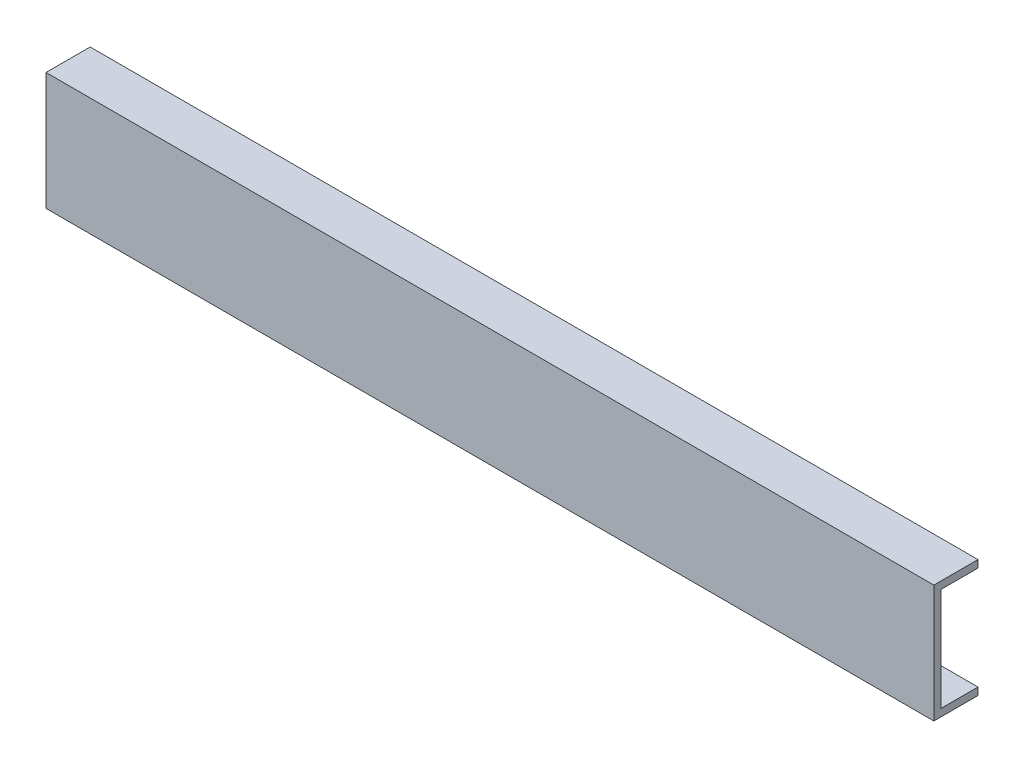
SolidWorks part; units mm, degrees
ref_plane "Front Plane" through (0, 0, 0) normal (0, 0, 1) x (1, 0, 0)
ref_plane "Top Plane" through (0, 0, 0) normal (0, 1, 0) x (1, 0, 0)
ref_plane "Right Plane" through (0, 0, 0) normal (1, 0, 0) x (0, 0, -1)
sketch "Sketch1" plane through (0, 0, 0) normal (1, 0, 0) x (0, 0, -1)
  line L0 (0, 65.8376) -> (30, 65.8376)
  line L1 (30, 65.8376) -> (30, 60.8376)
  line L2 (30, 60.8376) -> (5, 60.8376)
  line L3 (5, 60.8376) -> (5, -9.1624)
  line L4 (5, -9.1624) -> (30, -9.1624)
  line L5 (30, -9.1624) -> (30, -14.1624)
  line L6 (30, -14.1624) -> (0, -14.1624)
  line L7 (0, -14.1624) -> (0, 65.8376)
  dimension "D1" = 5
  dimension "D2" = 80
  dimension "D3" = 5
  dimension "D4" = 30
extrude "Boss-Extrude1" add sketch "Sketch1" along normal blind 603.25
